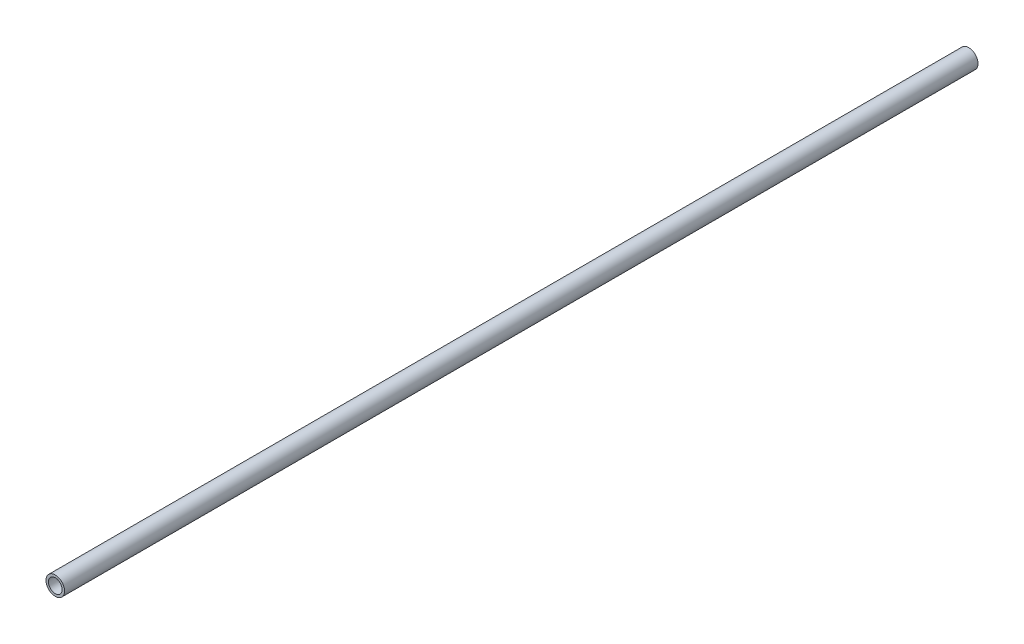
SolidWorks part; units mm, degrees
ref_plane "Front Plane" through (0, 0, 0) normal (0, 0, 1) x (1, 0, 0)
ref_plane "Top Plane" through (0, 0, 0) normal (0, 1, 0) x (1, 0, 0)
ref_plane "Right Plane" through (0, 0, 0) normal (1, 0, 0) x (0, 0, -1)
sketch "Sketch1" plane through (0, 0, 0) normal (0, 0, 1) x (1, 0, 0)
  circle A0 centre (0, 0) radius 10.668
  dimension "Pipe OD" = 21.336
extrude "Extrude-Thin1" add sketch "Sketch1" along normal mid plane 1050 thin thin type one direction reverse wall 2.7686
